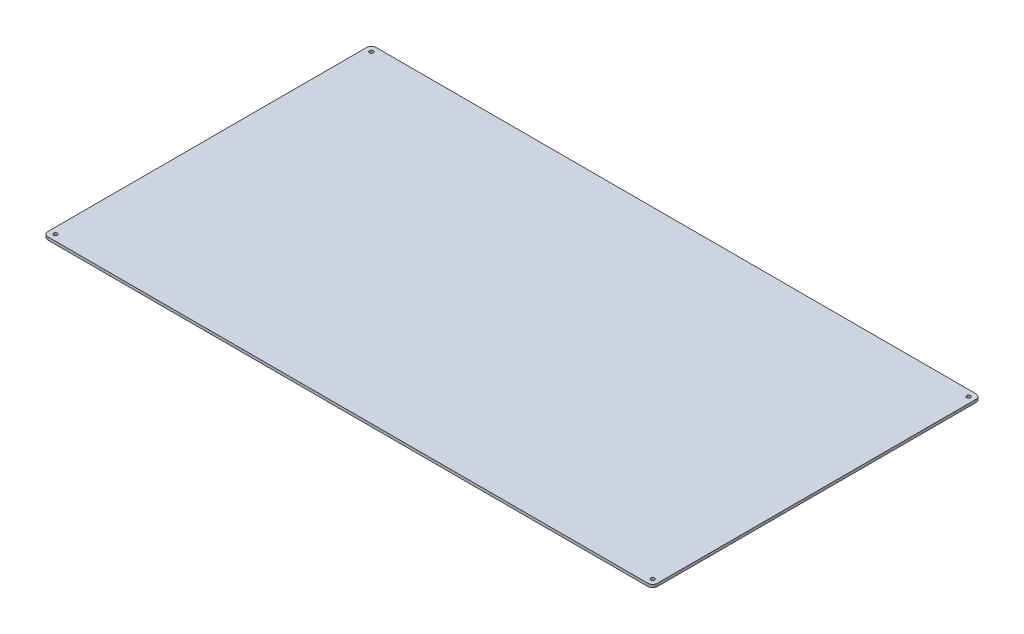
SolidWorks part; units mm, degrees
ref_plane "前视基准面" through (0, 0, 0) normal (0, 0, 1) x (1, 0, 0)
ref_plane "上视基准面" through (0, 0, 0) normal (0, 1, 0) x (1, 0, 0)
ref_plane "右视基准面" through (0, 0, 0) normal (1, 0, 0) x (0, 0, -1)
sketch "草图1" plane through (0, 0, 0) normal (0, 1, 0) x (1, 0, 0)
  line L5 (5, 0) -> (645, 0)
  line L6 (0, 5) -> (0, 345)
  line L7 (5, 350) -> (645, 350)
  line L8 (650, 5) -> (650, 345)
  arc A8 (650, 345) -> (645, 350) centre (645, 345) ccw
  arc A9 (645, 0) -> (650, 5) centre (645, 5) ccw
  arc A10 (5, 0) -> (0, 5) centre (5, 5) cw
  arc A11 (0, 345) -> (5, 350) centre (5, 345) cw
  circle A12 centre (6.5, 343.5) radius 2
  circle A13 centre (643.5, 343.5) radius 2
  circle A14 centre (643.5, 6.5) radius 2
  circle A15 centre (6.5, 6.5) radius 2
  point P7 (650, 350)
  point P12 (0, 0)
  point P15 (0, 350)
  point P25 (0, 0)
  point P27 (8.9894, 14.9881)
  dimension "D3" = 5
  dimension "D4" = 6.5
  dimension "D7" = 6.5
  dimension "D10" = 6.5
  dimension "D6" = 6.5
  dimension "D8" = 6.5
  dimension "D1" = 650
  dimension "D2" = 350
  dimension "D5" = 6.5
  dimension "D9" = 6.5
  dimension "D11" = 6.5
extrude "凸台-拉伸1" add sketch "草图1" along normal blind 3
